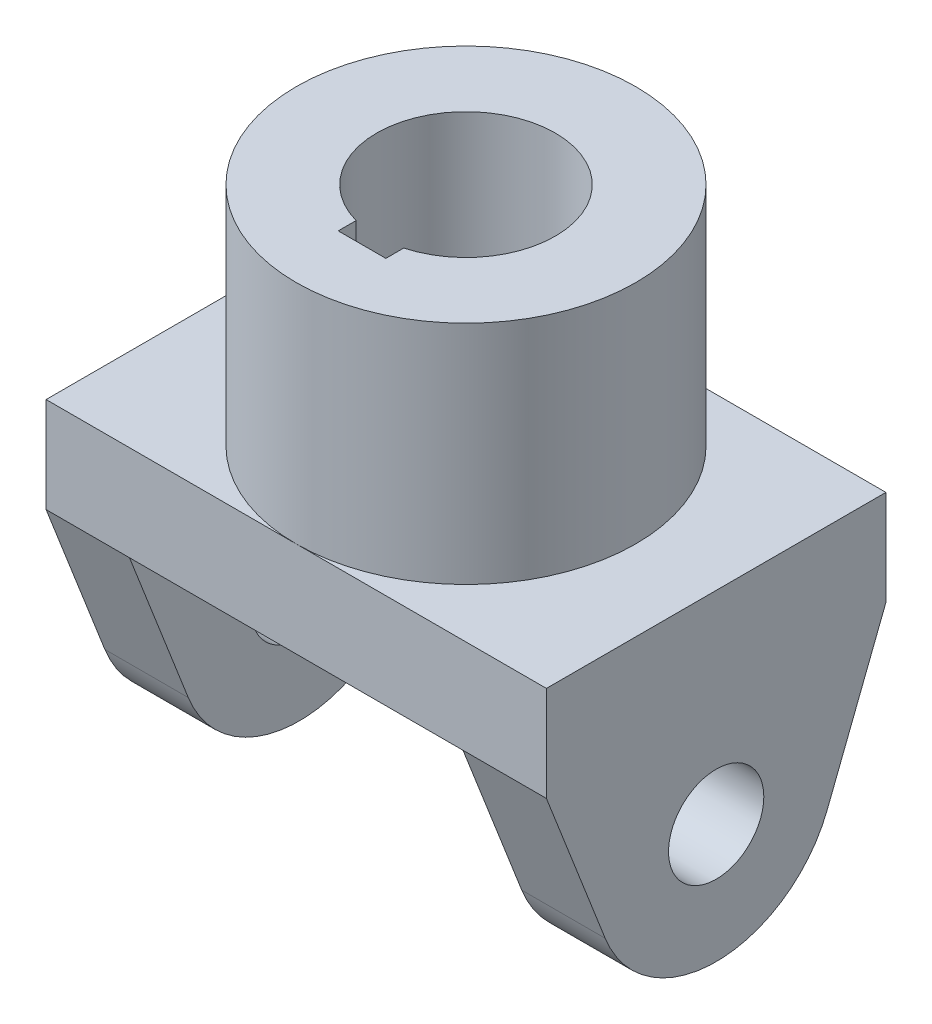
SolidWorks part; units mm, degrees
ref_plane "Front Plane" through (0, 0, 0) normal (0, 0, 1) x (1, 0, 0)
ref_plane "Top Plane" through (0, 0, 0) normal (0, 1, 0) x (1, 0, 0)
ref_plane "Right Plane" through (0, 0, 0) normal (1, 0, 0) x (0, 0, -1)
sketch "Sketch1" plane through (0, 0, 0) normal (0, 1, 0) x (1, 0, 0)
  circle A0 centre (0, 0) radius 28.5
  circle A1 centre (0, 0) radius 15
  dimension "D1" = 57
  dimension "D2" = 30
extrude "Boss-Extrude1" add sketch "Sketch1" along normal blind 38
sketch "Sketch2" plane through (0, 0, 0) normal (0, -1, 0) x (1, 0, 0)
  line L1 (-42, 28.5) -> (42, 28.5)
  line L2 (-42, 28.5) -> (-42, -28.5)
  line L3 (-42, -28.5) -> (42, -28.5)
  line L4 (42, 28.5) -> (42, -28.5)
  line L5 (-42, 28.5) -> (42, -28.5) construction
  line L6 (-42, -28.5) -> (42, 28.5) construction
  point P0 (0, 0)
  dimension "D1" = 57
  dimension "D2" = 84
extrude "Boss-Extrude2" add sketch "Sketch2" along normal blind 16
sketch "Sketch3" plane through (42, 0, 0) normal (1, 0, 0) x (0, 0, -1)
  line L0 (0, -16) -> (0, -34) construction
  line L1 (28.5, -16) -> (-28.5, -16) construction
  line L2 (28.5, 38) -> (-28.5, 38) construction
  line L3 (-28.5, -16) -> (-18.6299, -41.2751)
  line L4 (28.5, -16) -> (18.6299, -41.2751)
  line L5 (28.5, -16) -> (-28.5, -16)
  arc A0 (-18.6299, -41.2751) -> (18.6299, -41.2751) centre (0, -34) ccw
  circle A1 centre (0, -34) radius 8
  dimension "D1" = 40
  dimension "D2" = 16
  dimension "D3" = 72
extrude "Boss-Extrude3" add sketch "Sketch3" against normal blind 14
mirror "Mirror1" about plane through (0, 0, 0) normal (1, 0, 0) of "Boss-Extrude3"
sketch "Sketch4" plane through (0, 38, 0) normal (0, 1, 0) x (1, 0, 0)
  line L0 (0, 33.2273) -> (0, -38.2971) construction
  line L1 (-4, -14.4568) -> (-4, -17.4568)
  line L2 (-4, -17.4568) -> (4, -17.4568)
  line L3 (4, -17.4568) -> (4, -14.4568)
  circle A0 centre (0, 0) radius 15 construction
  circle A1 centre (0, 0) radius 15 construction
  arc A2 (-4, -14.4568) -> (4, -14.4568) centre (0, 0) ccw
  dimension "D1" = 3
  dimension "D2" = 8
  dimension "D3" = 4
extrude "Cut-Extrude1" cut sketch "Sketch4" against normal up to surface (38 mm away) up to face at (-28.125, 0, 0)
sketch "Sketch5" plane through (0, 0, 0) normal (0, 1, 0) x (1, 0, 0)
  circle A0 centre (0, 0) radius 15
  dimension "D1" = 30
extrude "Cut-Extrude2" cut sketch "Sketch5" against normal blind 38
